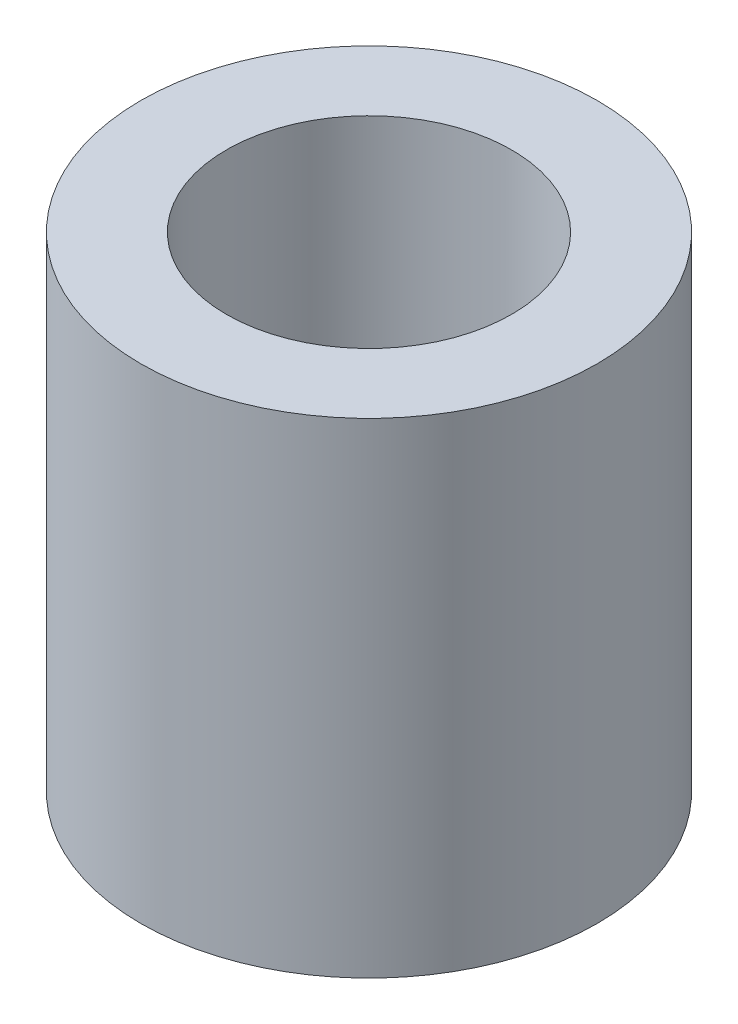
SolidWorks part; units mm, degrees
ref_plane "前视基准面" through (0, 0, 0) normal (0, 0, 1) x (1, 0, 0)
ref_plane "上视基准面" through (0, 0, 0) normal (0, 1, 0) x (1, 0, 0)
ref_plane "右视基准面" through (0, 0, 0) normal (1, 0, 0) x (0, 0, -1)
other "Configuration Table"
sketch "草图1" plane through (0, 0, 0) normal (0, 1, 0) x (1, 0, 0)
  circle A0 centre (0, 0) radius 2.5
  circle A1 centre (0, 0) radius 4
  dimension "D1" = 5
  dimension "D2" = 8
extrude "凸台-拉伸1" add sketch "草图1" along normal blind 8.5
